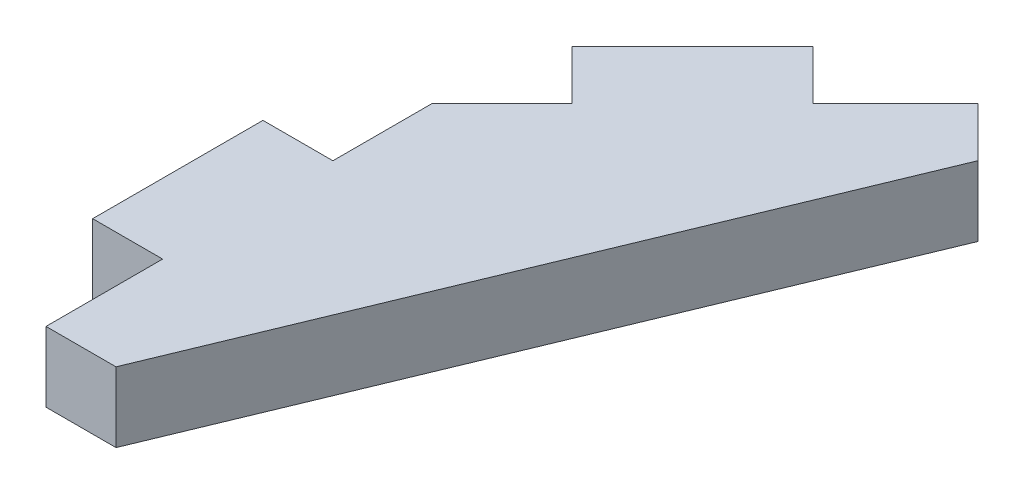
SolidWorks part; units mm, degrees
ref_plane "Plan de face" through (0, 0, 0) normal (0, 0, 1) x (1, 0, 0)
ref_plane "Plan de dessus" through (0, 0, 0) normal (0, 1, 0) x (1, 0, 0)
ref_plane "Plan de droite" through (0, 0, 0) normal (1, 0, 0) x (0, 0, -1)
sketch "Esquisse1" plane through (0, 0, 0) normal (0, 1, 0) x (1, 0, 0)
  line L0 (13.8245, 9.5808) -> (3.0008, -16.55)
  line L1 (3.0008, -16.55) -> (0, -16.55)
  line L2 (0, -16.55) -> (0, -11.55)
  line L3 (0, -11.55) -> (-3, -11.55)
  line L4 (-3, -11.55) -> (-3, -4.25)
  line L5 (-3, -4.25) -> (0, -4.25)
  line L6 (0, -4.25) -> (0, 0)
  line L7 (0, 0) -> (3.0052, 3.0052)
  line L8 (3.0052, 3.0052) -> (0.8839, 5.1265)
  line L9 (0.8839, 5.1265) -> (6.0458, 10.2884)
  line L10 (6.0458, 10.2884) -> (8.1671, 8.1671)
  line L11 (8.1671, 8.1671) -> (11.7026, 11.7026)
  line L12 (11.7026, 11.7026) -> (13.8245, 9.5808)
  point P11 (15.7202, 4.9239)
  point P14 (13.5066, 1.6712)
  point P15 (12.8979, -0.981)
  point P16 (0, 0)
  point P18 (18.0507, -5.9314)
  point P19 (3.8444, -16.0973)
  point P20 (12.8526, 9.1046)
  point P21 (22.1617, 2.4249)
  point P22 (-10.6452, 7.4888)
  point P23 (-0.9961, -10.8809)
  point P24 (20.3205, 4.2995)
  point P25 (13.7359, 3.0008)
  point P26 (13.4415, 3.0008)
  point P27 (0, 12.4328)
  point P28 (-12.5377, 9.8479)
  point P29 (-9.1349, 7.1322)
  point P30 (-9.1991, 13.4428)
  point P31 (0.1964, -16.4966)
  dimension "D1" = 4.25
  dimension "D2" = 5
  dimension "D3" = 3
  dimension "D4" = 7.3
  dimension "D5" = 3.0008
  dimension "D6" = 135
extrude "Boss.-Extru.1" add sketch "Esquisse1" along normal blind 3
